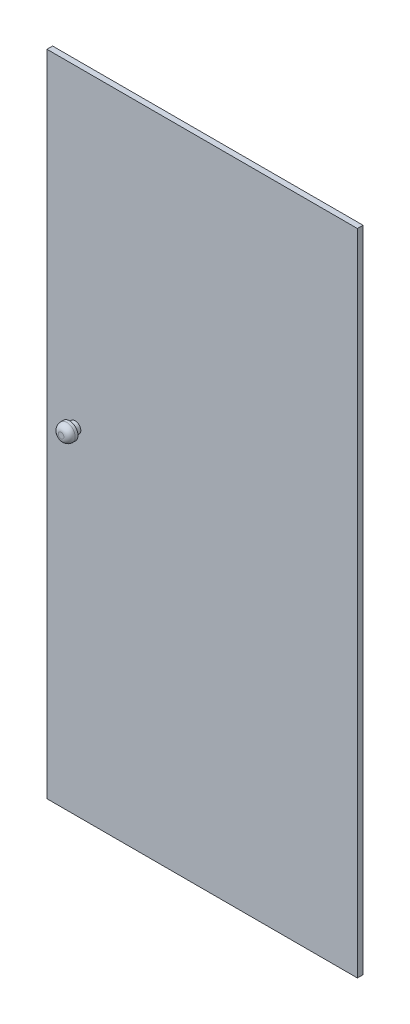
SolidWorks part; units mm, degrees
ref_plane "Front Plane" through (0, 0, 0) normal (0, 0, 1) x (1, 0, 0)
ref_plane "Top Plane" through (0, 0, 0) normal (0, 1, 0) x (1, 0, 0)
ref_plane "Right Plane" through (0, 0, 0) normal (1, 0, 0) x (0, 0, -1)
sketch "Sketch1" plane through (0, 0, 0) normal (0, 0, 1) x (1, 0, 0)
  line L1 (275, -575) -> (-275, -575)
  line L2 (275, -575) -> (275, 575)
  line L3 (275, 575) -> (-275, 575)
  line L4 (-275, -575) -> (-275, 575)
  line L5 (275, -575) -> (-275, 575) construction
  line L6 (275, 575) -> (-275, -575) construction
  point P0 (0, 0)
extrude "Boss-Extrude1" add sketch "Sketch1" along normal blind 10
sketch "Sketch2" plane through (0, 0, 10) normal (0, 0, 1) x (1, 0, 0)
  circle A0 centre (-225, 20) radius 10
extrude "Boss-Extrude2" add sketch "Sketch2" along normal blind 10
sketch "Sketch3" plane through (0, 0, 20) normal (0, 0, 1) x (1, 0, 0)
  circle A0 centre (-225, 20) radius 15
extrude "Boss-Extrude3" add sketch "Sketch3" along normal blind 15
fillet "Fillet4" radius 10 1 edges at (-210, 20, 35)
